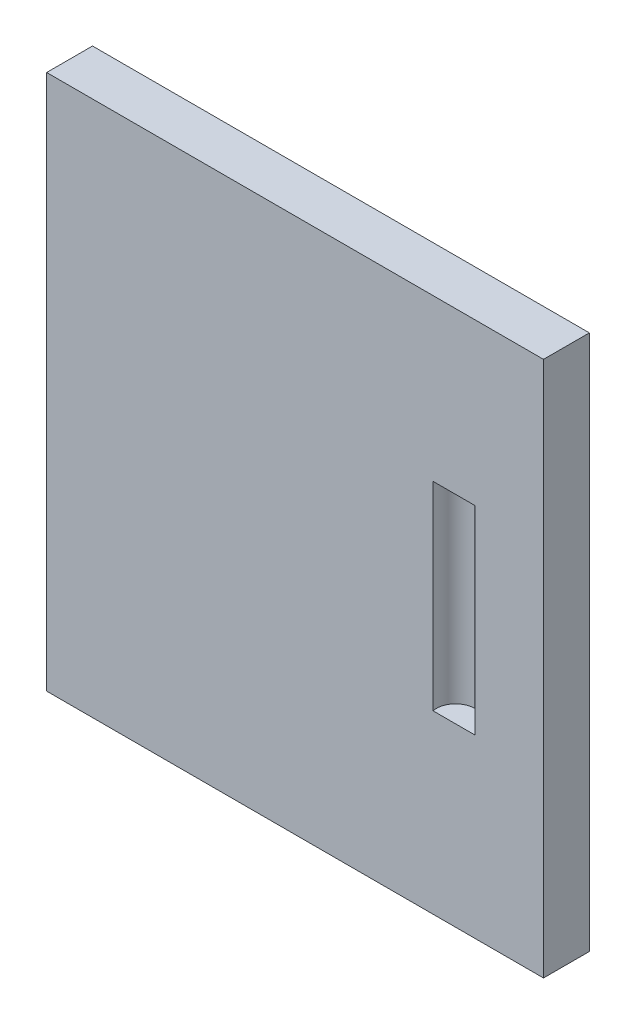
SolidWorks part; units mm, degrees
material "Teak"
ref_plane "Front Plane" through (0, 0, 0) normal (0, 0, 1) x (1, 0, 0)
ref_plane "Top Plane" through (0, 0, 0) normal (0, 1, 0) x (1, 0, 0)
ref_plane "Right Plane" through (0, 0, 0) normal (1, 0, 0) x (0, 0, -1)
sketch "Sketch1" plane through (0, 0, 0) normal (0, 0, 1) x (1, 0, 0)
  line L1 (162.5, -200) -> (-162.5, -200)
  line L2 (162.5, -200) -> (162.5, 200)
  line L3 (162.5, 200) -> (-162.5, 200)
  line L4 (-162.5, -200) -> (-162.5, 200)
  line L5 (162.5, -200) -> (-162.5, 200) construction
  line L6 (162.5, 200) -> (-162.5, -200) construction
  point P0 (0, 0)
  dimension "D1" = 325
  dimension "D2" = 400
extrude "Boss-Extrude1" add sketch "Sketch1" along normal mid plane 30
sketch "Sketch2" plane through (0, 0, -15) normal (0, 0, -1) x (-1, 0, 0)
  line L0 (-162.5, 200) -> (162.5, 200) construction
  line L1 (162.5, 200) -> (162.5, -200) construction
  circle A0 centre (155, 135) radius 2.5
  circle A1 centre (140, 115) radius 2.5
  circle A2 centre (155, 95) radius 2.5
  dimension "D5" = 5
  dimension "D1" = 65
  dimension "D2" = 7.5
  dimension "D3" = 40
  dimension "D4" = 15
  dimension "D6" = 20
extrude "Cut-Extrude1" cut sketch "Sketch2" against normal blind 10
mirror "Mirror1" about plane through (0, 0, 0) normal (0, 1, 0) of "Cut-Extrude1"
sketch "Sketch4" plane through (0, 0, 15) normal (0, 0, 1) x (1, 0, 0)
  line L1 (-162.5, 200) -> (165.9726, 200)
  line L2 (-162.5, 200) -> (-162.5, 150.46)
  line L3 (-162.5, 150.46) -> (165.9726, 150.46)
  line L4 (165.9726, 200) -> (165.9726, 150.46)
  dimension "D1" = 49.54
extrude "Cut-Extrude3" cut sketch "Sketch4" against normal through all
ref_plane "Plane1" through (0, -19.77, 0) normal (0, 1, 0) x (1, 0, 0)
sketch "Sketch5" plane through (0, -19.77, 0) normal (0, 1, 0) x (1, 0, 0)
  line L0 (102.5, 0) -> (120.5, 0)
  line L1 (124.0503, -8.5207) -> (111.3757, -21.3018)
  arc A0 (111.3757, -21.3018) -> (102.5, 0) centre (102.5, -12.5) cw
  arc A1 (120.5, 0) -> (124.0503, -8.5207) centre (120.5, -5) cw
  dimension "D3" = 12.5
  dimension "D5" = 5
extrude "Cut-Extrude4" cut sketch "Sketch5" against normal mid plane 130
mirror "Mirror2" about plane through (0, -19.77, 0) normal (0, 1, 0) of "Mirror1", "Cut-Extrude1"
sketch "Sketch6" plane through (0, 0, -15) normal (0, 0, -1) x (-1, 0, 0)
  circle A0 centre (140, 115) radius 2.5
  circle A1 centre (155, 135) radius 2.5
  circle A2 centre (140, -154.54) radius 2.5
  circle A3 centre (155, -174.54) radius 2.5
  point P12 (0, 0)
extrude "Boss-Extrude4" add sketch "Sketch6" against normal through all contours A0 | A1 | A2 | A3
